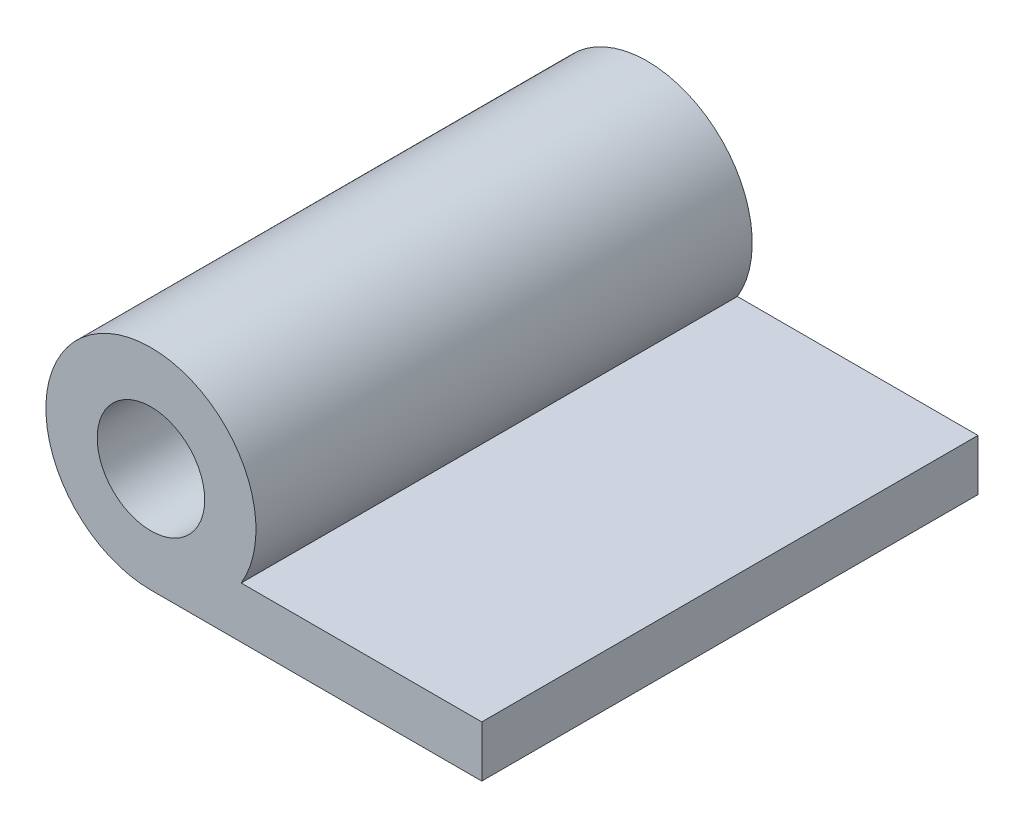
SolidWorks part; units mm, degrees
material "AISI 1020"
ref_plane "Plano frontal" through (0, 0, 0) normal (0, 0, 1) x (1, 0, 0)
ref_plane "Plano superior" through (0, 0, 0) normal (0, 1, 0) x (1, 0, 0)
ref_plane "Plano direito" through (0, 0, 0) normal (1, 0, 0) x (0, 0, -1)
sketch "Esboço1" plane through (0, 0, 0) normal (0, 0, 1) x (1, 0, 0)
  circle A0 centre (0, 0) radius 3.25
  circle A1 centre (0, 0) radius 6.35
  dimension "D1" = 12.7
  dimension "D2" = 6.5
extrude "Ressalto-extrusão1" add sketch "Esboço1" along normal mid plane 30
sketch "Esboço2" plane through (0, 0, 15) normal (0, 0, 1) x (1, 0, 0)
  line L1 (0, -6.35) -> (20, -6.35)
  line L2 (0, -6.35) -> (0, -3.25)
  line L3 (0, -3.25) -> (20, -3.25)
  line L4 (20, -6.35) -> (20, -3.25)
  circle A0 centre (0, 0) radius 6.35 construction
  circle A1 centre (0, 0) radius 3.25 construction
  dimension "D1" = 20
extrude "Ressalto-extrusão2" add sketch "Esboço2" against normal up to surface (30 mm away) up to face at (6.35, 0, -15)
